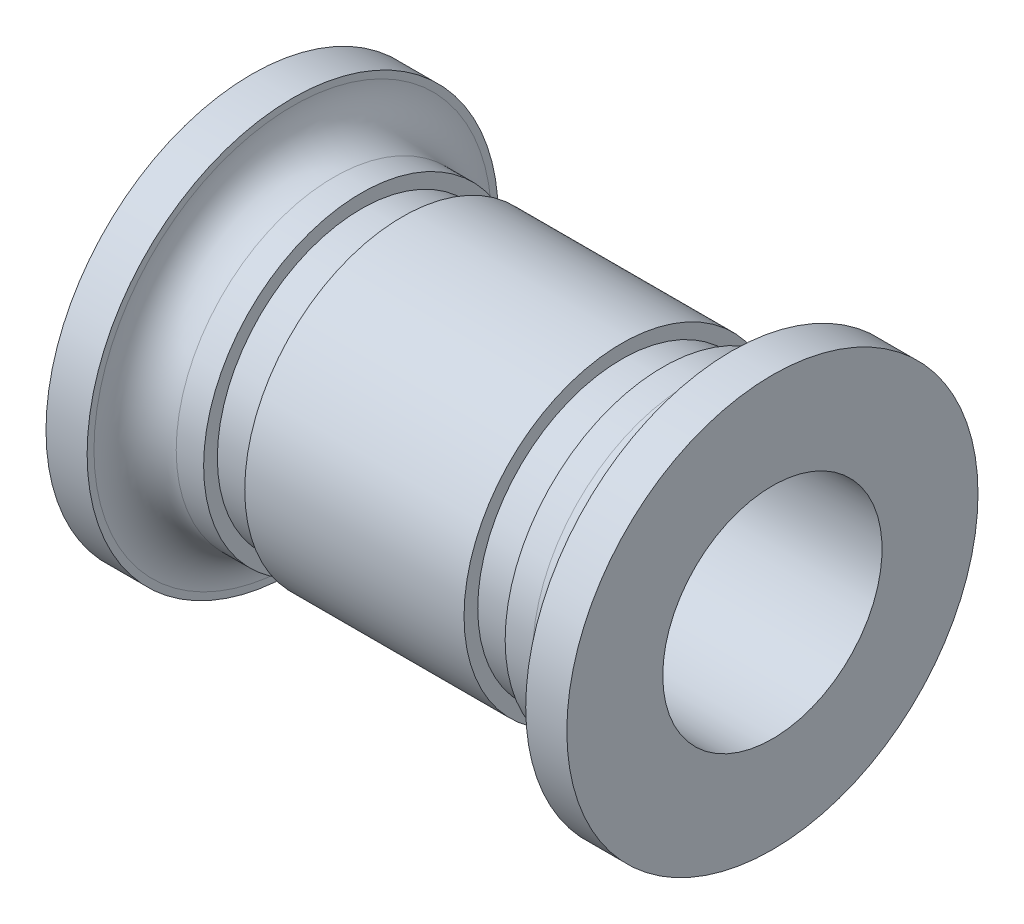
SolidWorks part; units mm, degrees
material "Commercialement pur CP-Ti UNS R50400 (SS)"
ref_plane "Plan de face" through (0, 0, 0) normal (0, 0, 1) x (1, 0, 0)
ref_plane "Plan de dessus" through (0, 0, 0) normal (0, 1, 0) x (1, 0, 0)
ref_plane "Plan de droite" through (0, 0, 0) normal (1, 0, 0) x (0, 0, -1)
sketch "Esquisse2" plane through (0, 0, 0) normal (0, 0, 1) x (1, 0, 0)
  line L0 (0, 150) -> (30, 150) construction
  line L1 (0, 0) -> (265, 0)
  line L9 (0, 115) -> (80, 115) construction
  line L10 (0, 150) -> (0, 80)
  line L11 (380, 150) -> (380, 80)
  line L12 (0, 150) -> (30, 150)
  line L13 (380, 150) -> (350, 150)
  line L14 (270, 115) -> (110, 115)
  line L15 (0, 150) -> (0, 80)
  line L17 (80, 115) -> (80, 105)
  line L18 (80, 105) -> (110, 105)
  line L19 (110, 115) -> (110, 105)
  line L21 (300, 115) -> (300, 105)
  line L22 (300, 105) -> (270, 105)
  line L23 (270, 115) -> (270, 105)
  line L24 (0, 80) -> (380, 80)
  line L25 (110, 115) -> (270, 115) construction
  line L26 (300, 115) -> (265, 115) construction
  line L29 (30, 150) -> (30, 145)
  line L30 (60, 115) -> (80, 115)
  line L32 (300, 115) -> (320, 115)
  line L35 (350, 145) -> (350, 150)
  line L36 (350, 150) -> (380, 150) construction
  arc A0 (30, 145) -> (60, 115) centre (60, 145) ccw
  arc A1 (320, 115) -> (350, 145) centre (320, 145) ccw
  point P25 (30, 115)
  dimension "D5" = 30
  dimension "D14" = 30
  dimension "D1" = 80
  dimension "D2" = 35
  dimension "D3" = 30
  dimension "D4" = 70
  dimension "D6" = 30
  dimension "D7" = 220
  dimension "D8" = 50
  dimension "D9" = 50
  dimension "D10" = 10
  dimension "D11" = 10
  dimension "D12" = 30
  dimension "D13" = 30
revolve "Révolution1" add sketch "Esquisse2" angle 360 about L1
